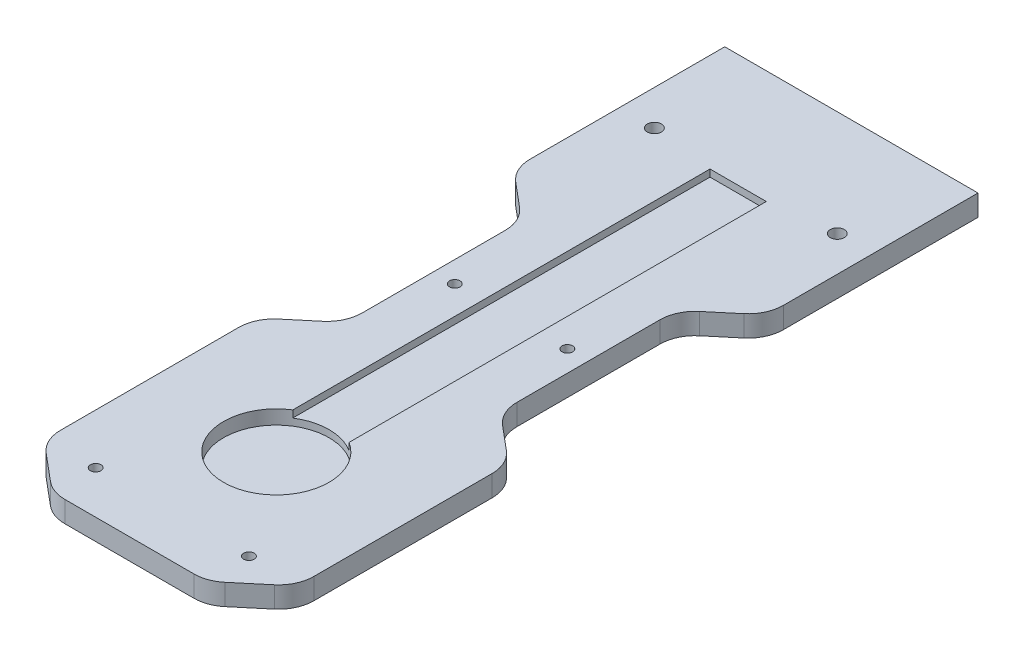
SolidWorks part; units mm, degrees
ref_plane "Front Plane" through (0, 0, 0) normal (0, 0, 1) x (1, 0, 0)
ref_plane "Top Plane" through (0, 0, 0) normal (0, 1, 0) x (1, 0, 0)
ref_plane "Right Plane" through (0, 0, 0) normal (1, 0, 0) x (0, 0, -1)
sketch "Sketch1" plane through (0, 0, 0) normal (0, 1, 0) x (1, 0, 0)
  line L0 (21.2131, -102.2276) -> (35.2131, -90.4802)
  line L1 (35.2131, -90.4802) -> (35.2131, -30.4802)
  line L2 (35.2131, -30.4802) -> (21.2131, -18.7328)
  line L3 (21.2131, -18.7328) -> (21.2131, 31.2672)
  line L4 (21.2131, 31.2672) -> (35.2131, 43.0146)
  line L5 (35.2131, 43.0146) -> (35.2131, 103.0146)
  line L6 (35.2131, 103.0146) -> (-36.7869, 103.0146)
  line L7 (-36.7869, 103.0146) -> (-36.7869, 43.0146)
  line L8 (-36.7869, 43.0146) -> (-22.7869, 31.2672)
  line L9 (-22.7869, 31.2672) -> (-22.7869, -18.7328)
  line L10 (-22.7869, -18.7328) -> (-36.7869, -30.4802)
  line L11 (-36.7869, -30.4802) -> (-36.7869, -90.4802)
  line L12 (-36.7869, -90.4802) -> (-22.7869, -102.2276)
  line L13 (-22.7869, -102.2276) -> (21.2131, -102.2276)
extrude "Boss-Extrude1" add sketch "Sketch1" along normal blind 6
fillet "Fillet1" radius 10 8 edges at (35.2131, 3, 30.4802) (21.2131, 3, 18.7328) (-22.7869, 3, 18.7328) (-36.7869, 3, 30.4802) (35.2131, 3, 90.4802) (21.2131, 3, 102.2276) (-22.7869, 3, 102.2276) (-36.7869, 3, 90.4802)
sketch "Sketch2" plane through (0, 0, 0) normal (0, -1, 0) x (1, 0, 0)
  line L1 (-36.7869, 60.4802) -> (21.737, 60.4802) construction
  line L2 (-36.7869, 35.1433) -> (-36.7869, 85.8172) construction
  circle A0 centre (-0.7869, 60.4802) radius 2.5
  dimension "D2" = 5
  dimension "D1" = 36
extrude "Cut-Extrude1" cut sketch "Sketch2" against normal blind 6
sketch "Sketch4" plane through (0, 0, 0) normal (0, -1, 0) x (1, 0, 0)
  line L0 (35.2131, -43.0146) -> (35.2131, -103.0146) construction
  line L1 (-36.7869, -103.0146) -> (35.2131, -103.0146)
  line L2 (-36.7869, -103.0146) -> (-36.7869, -99.0146)
  line L3 (-36.7869, -99.0146) -> (35.2131, -99.0146)
  line L4 (35.2131, -103.0146) -> (35.2131, -99.0146)
  dimension "D1" = 4
sketch "Sketch5" plane through (0, 0, 0) normal (0, -1, 0) x (1, 0, 0)
  circle A0 centre (-0.7869, 60.4802) radius 7.5
  dimension "D1" = 15
sketch "Sketch8" plane through (0, 6, 0) normal (0, 1, 0) x (1, 0, 0)
  line L0 (-8.7869, -50.8756) -> (7.2131, -50.8756)
  line L2 (-8.7869, -50.8756) -> (7.2131, -50.8756)
  line L3 (-8.7869, -50.8756) -> (-8.7869, 70.8241)
  line L4 (-8.7869, 70.8241) -> (7.2131, 70.8241)
  line L5 (7.2131, -50.8756) -> (7.2131, 70.8241)
  dimension "D2" = 16
  dimension "D3" = 16
extrude "Cut-Extrude5" cut sketch "Sketch8" against normal blind 2 contours L0 L5 L4 L3
sketch "Sketch9" plane through (0, 6, 0) normal (0, 1, 0) x (1, 0, 0)
  circle A0 centre (-0.7869, -60.4802) radius 15
  dimension "D1" = 30
extrude "Cut-Extrude6" cut sketch "Sketch9" against normal blind 4
sketch "Sketch10" plane through (0, 2, 0) normal (0, 1, 0) x (1, 0, 0)
  circle A0 centre (-0.7869, -60.4802) radius 4.4604
extrude "Boss-Extrude2" add sketch "Sketch10" against normal blind 2
fillet "Fillet2" radius 10 4 edges at (35.2131, 3, -43.0146) (21.2131, 3, -31.2672) (-36.7869, 3, -43.0146) (-22.7869, 3, -31.2672)
sketch "Sketch12" plane through (0, 6, 0) normal (0, 1, 0) x (1, 0, 0)
  circle A0 centre (15.2131, 6.2672) radius 1.5
  circle A1 centre (-16.7869, 6.2672) radius 1.5
extrude "Cut-Extrude7" cut sketch "Sketch12" against normal blind 10
sketch "Sketch13" plane through (0, 0, 0) normal (0, -1, 0) x (1, 0, 0)
  line L0 (-0.7869, 102.2276) -> (-0.7869, 79.8851) construction
  line L1 (-19.1472, 102.2276) -> (17.5734, 102.2276) construction
  circle A0 centre (-22.5674, 90.0433) radius 1.5
  arc A2 (-33.2148, 93.4776) -> (-36.7869, 85.8172) centre (-26.7869, 85.8172) ccw construction
  arc A3 (-19.1472, 102.2276) -> (-25.5751, 99.8881) centre (-19.1472, 92.2276) ccw construction
  circle A4 centre (20.9936, 90.0433) radius 1.5
  point P7 (-35.85, 90.0433)
  point P11 (-22.5674, 101.6246)
  dimension "D1" = 3
extrude "Cut-Extrude8" cut sketch "Sketch13" against normal blind 10
sketch "Sketch14" plane through (0, 0, 0) normal (0, -1, 0) x (1, 0, 0)
  line L0 (35.2131, -103.0146) -> (-36.7869, -103.0146) construction
  line L1 (-36.7869, -103.0146) -> (-36.7869, -47.6776) construction
  line L2 (35.2131, -47.6776) -> (35.2131, -103.0146) construction
  circle A0 centre (-26.7869, -73.0146) radius 2
  circle A1 centre (25.2131, -73.0146) radius 2
  dimension "D1" = 4
  dimension "D4" = 10
  dimension "D5" = 30
  dimension "D6" = 4
  dimension "D2" = 30
  dimension "D3" = 10
extrude "Cut-Extrude9" cut sketch "Sketch14" against normal blind 10
